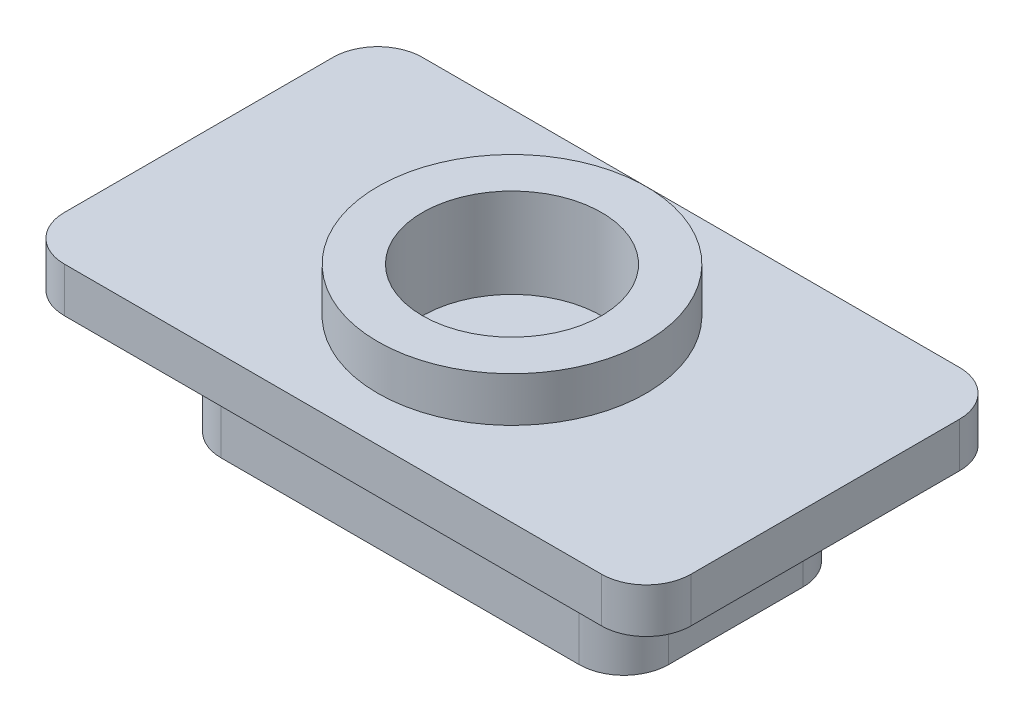
SolidWorks part; units mm, degrees
ref_plane "Alzado" through (0, 0, 0) normal (0, 0, 1) x (1, 0, 0)
ref_plane "Planta" through (0, 0, 0) normal (0, 1, 0) x (1, 0, 0)
ref_plane "Vista lateral" through (0, 0, 0) normal (1, 0, 0) x (0, 0, -1)
sketch "Croquis1" plane through (0, 0, 0) normal (0, 1, 0) x (1, 0, 0)
  line L1 (-4, -2.5) -> (4, -2.5)
  line L2 (-5, -1.5) -> (-5, 1.5)
  line L3 (-4, 2.5) -> (4, 2.5)
  line L4 (5, -1.5) -> (5, 1.5)
  line L5 (-5, -2.5) -> (5, 2.5) construction
  line L6 (-5, 2.5) -> (5, -2.5) construction
  arc A0 (4, -2.5) -> (5, -1.5) centre (4, -1.5) ccw
  arc A1 (-4, -2.5) -> (-5, -1.5) centre (-4, -1.5) cw
  arc A2 (-5, 1.5) -> (-4, 2.5) centre (-4, 1.5) cw
  arc A3 (4, 2.5) -> (5, 1.5) centre (4, 1.5) cw
  point P0 (0, 0)
  dimension "D1" = 1
  dimension "D2" = 10
  dimension "D3" = 5
extrude "Saliente-Extruir1" add sketch "Croquis1" along normal blind 2.5
sketch "Croquis2" plane through (0, 2.5, 0) normal (0, 1, 0) x (1, 0, 0)
  line L1 (-6, -4) -> (6, -4)
  line L2 (-7, -3) -> (-7, 3)
  line L3 (-6, 4) -> (6, 4)
  line L4 (7, -3) -> (7, 3)
  line L5 (-7, -4) -> (7, 4) construction
  line L6 (-7, 4) -> (7, -4) construction
  arc A0 (-7, 3) -> (-6, 4) centre (-6, 3) cw
  arc A1 (-6, -4) -> (-7, -3) centre (-6, -3) cw
  arc A2 (6, -4) -> (7, -3) centre (6, -3) ccw
  arc A3 (6, 4) -> (7, 3) centre (6, 3) cw
  point P0 (0, 0)
  dimension "D3" = 1
  dimension "D1" = 14
  dimension "D2" = 8
extrude "Saliente-Extruir2" add sketch "Croquis2" along normal blind 1
sketch "Croquis3" plane through (0, 3.5, 0) normal (0, 1, 0) x (1, 0, 0)
  circle A0 centre (0, 0) radius 3
  dimension "D1" = 6
extrude "Saliente-Extruir3" add sketch "Croquis3" along normal blind 1
sketch "Croquis4" plane through (0, 4.5, 0) normal (0, 1, 0) x (1, 0, 0)
  circle A0 centre (0, 0) radius 2
  dimension "D1" = 4
extrude "Cortar-Extruir1" cut sketch "Croquis4" against normal blind 2
